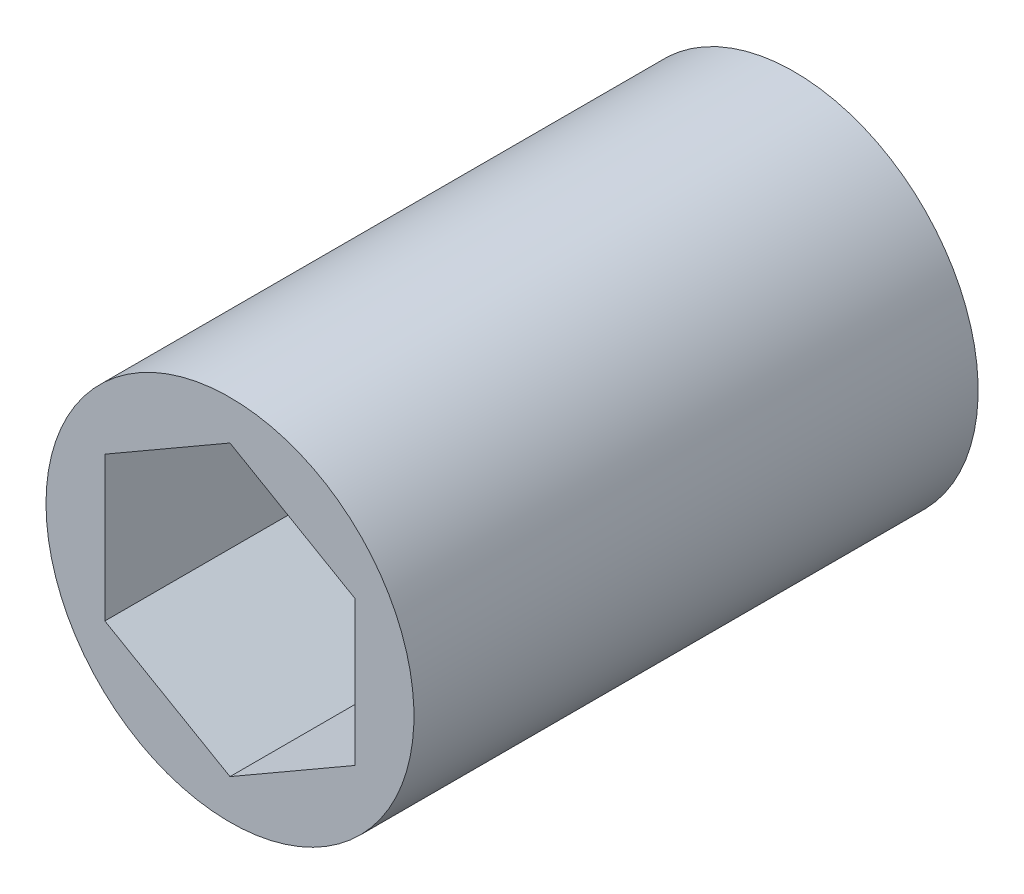
SolidWorks part; units mm, degrees
material "PET"
ref_plane "Front Plane" through (0, 0, 0) normal (0, 0, 1) x (1, 0, 0)
ref_plane "Top Plane" through (0, 0, 0) normal (0, 1, 0) x (1, 0, 0)
ref_plane "Right Plane" through (0, 0, 0) normal (1, 0, 0) x (0, 0, -1)
sketch "Sketch1" plane through (0, 0, 0) normal (0, 0, 1) x (1, 0, 0)
  line L1 (0, 7.479) -> (-6.477, 3.7395)
  line L2 (-6.477, 3.7395) -> (-6.477, -3.7395)
  line L3 (-6.477, -3.7395) -> (0, -7.479)
  line L4 (0, -7.479) -> (6.477, -3.7395)
  line L5 (6.477, -3.7395) -> (6.477, 3.7395)
  line L6 (6.477, 3.7395) -> (0, 7.479)
  circle A0 centre (0, 0) radius 6.477 construction
  circle A1 centre (0, 0) radius 9.525
  dimension "D1" = 12.954
  dimension "D2" = 19.05
extrude "Boss-Extrude1" add sketch "Sketch1" along normal mid plane 29.21
